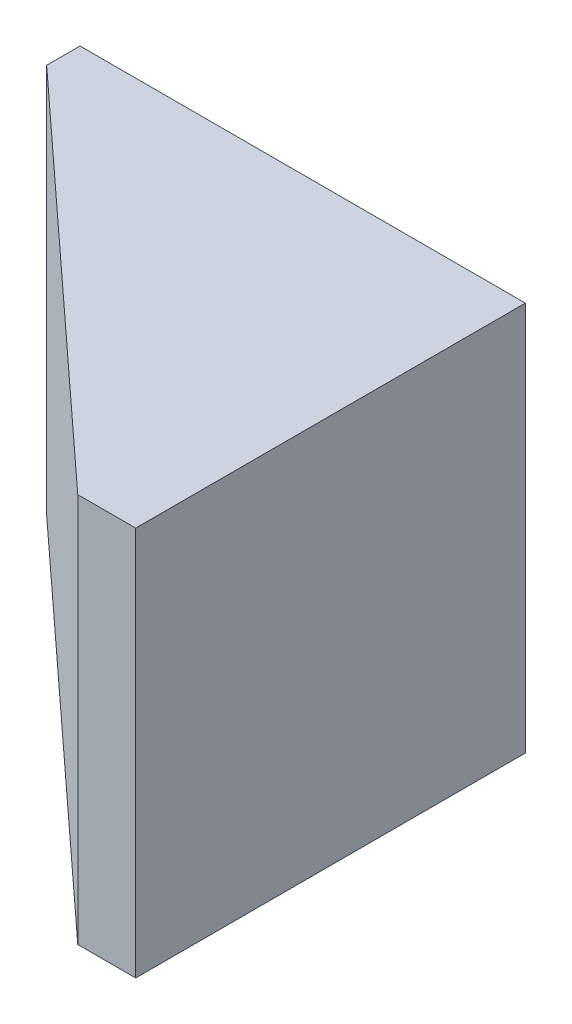
SolidWorks part; units mm, degrees
ref_plane "Front Plane" through (0, 0, 0) normal (0, 0, 1) x (1, 0, 0)
ref_plane "Top Plane" through (0, 0, 0) normal (0, 1, 0) x (1, 0, 0)
ref_plane "Right Plane" through (0, 0, 0) normal (1, 0, 0) x (0, 0, -1)
sketch "Sketch1" plane through (0, 0, 0) normal (0, 1, 0) x (1, 0, 0)
  line L0 (0, 0) -> (0, -6)
  line L1 (0, -6) -> (69.5919, -70)
  line L2 (69.5919, -70) -> (80, -70)
  line L3 (80, -70) -> (80, 0)
  line L4 (80, 0) -> (0, 0)
  dimension "D1" = 80
  dimension "D2" = 6
  dimension "D3" = 70
extrude "Boss-Extrude1" add sketch "Sketch1" along normal blind 70
